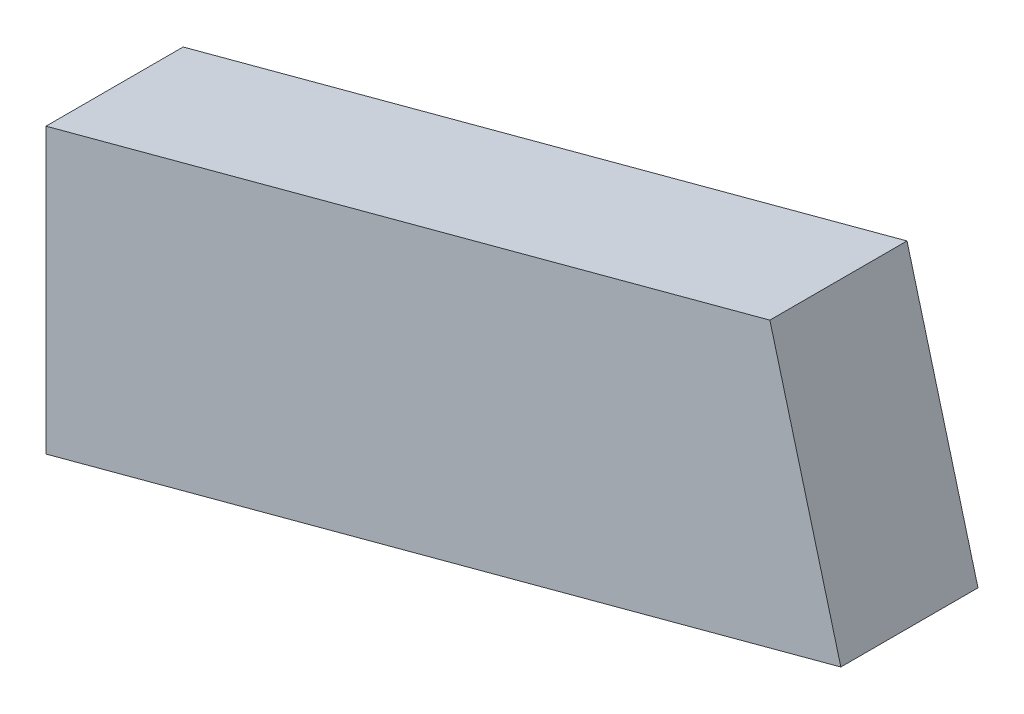
SolidWorks part; units mm, degrees
ref_plane "Front Plane" through (0, 0, 0) normal (0, 0, 1) x (1, 0, 0)
ref_plane "Top Plane" through (0, 0, 0) normal (0, 1, 0) x (1, 0, 0)
ref_plane "Right Plane" through (0, 0, 0) normal (1, 0, 0) x (0, 0, -1)
sketch "Croquis1" plane through (0, 0, 0) normal (0, 0, 1) x (1, 0, 0)
  line L0 (-13.0127, 43.7729) -> (-13.0127, 17.4769)
  line L1 (-13.0127, 43.7729) -> (54.0168, 61.7334)
  line L2 (54.0168, 61.7334) -> (60.5908, 37.1989)
  line L3 (60.5908, 37.1989) -> (-13.0127, 17.4769)
  dimension "D1" = 76.2
  dimension "D2" = 25.4
  dimension "D3" = 75
extrude "Saliente-Extruir3" add sketch "Croquis1" along normal blind 12.7 contours L0 L3 L2 L1
